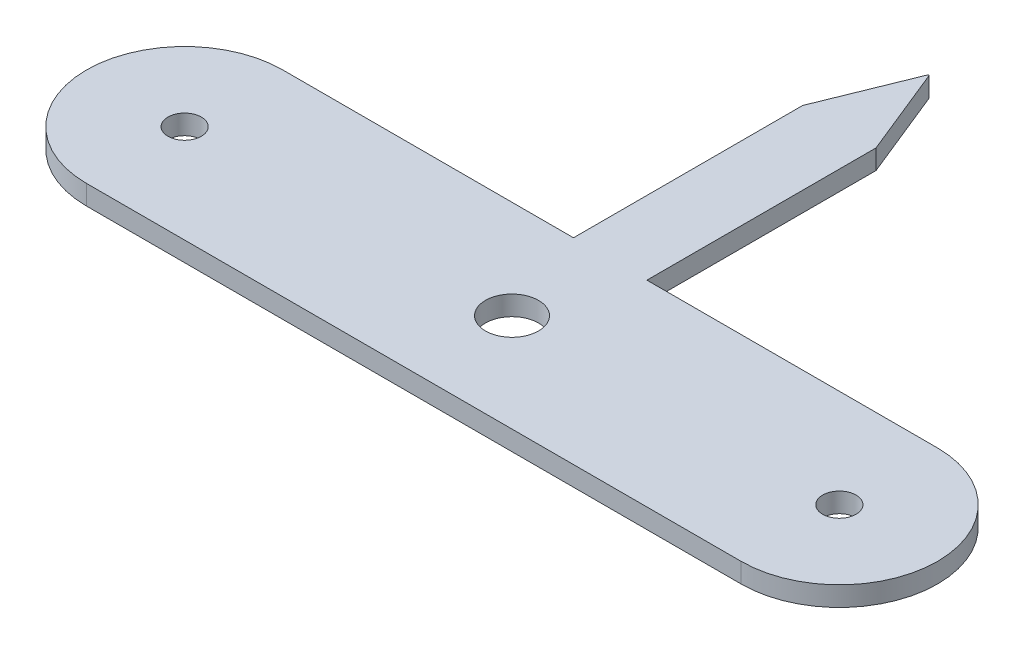
SolidWorks part; units mm, degrees
ref_plane "Front Plane" through (0, 0, 0) normal (0, 0, 1) x (1, 0, 0)
ref_plane "Top Plane" through (0, 0, 0) normal (0, 1, 0) x (1, 0, 0)
ref_plane "Right Plane" through (0, 0, 0) normal (1, 0, 0) x (0, 0, -1)
sketch "Sketch1" plane through (0, 0, 0) normal (0, 1, 0) x (1, 0, 0)
  line L0 (50, 0) -> (-50, 0) construction
  line L1 (50, -15) -> (-50, -15)
  line L2 (50, 15) -> (5.6066, 15)
  line L3 (-5.6066, 15) -> (-50, 15)
  line L5 (5.6066, 15) -> (5.6066, 50)
  line L7 (-5.6066, 15) -> (-5.6066, 50)
  line L8 (0, 0) -> (-5.6066, 50) construction
  line L9 (5.6066, 50) -> (0, 0) construction
  line L10 (-5.6066, 50) -> (0, 63.8402)
  line L11 (0, 63.8402) -> (5.6066, 50)
  arc A0 (50, -15) -> (50, 15) centre (50, 0) ccw
  arc A1 (-50, 15) -> (-50, -15) centre (-50, 0) ccw
  point P2 (0, 0)
  point P9 (0, 0)
  dimension "D1" = 100
  dimension "D2" = 30
  dimension "D3" = 35
extrude "Boss-Extrude1" add sketch "Sketch1" along normal blind 3
sketch "Sketch2" plane through (0, 3, 0) normal (0, 1, 0) x (1, 0, 0)
  line L0 (0, -1.65) -> (0, 1.65) construction
  circle A0 centre (0, 0) radius 4.05
  circle A1 centre (-50, 0) radius 2.55
  arc A2 (-50, 15) -> (-50, -15) centre (-50, 0) ccw construction
  circle A3 centre (50, 0) radius 2.55
  dimension "D1" = 5.1
  dimension "D2" = 8.1
extrude "Cut-Extrude1" cut sketch "Sketch2" against normal blind 3
fillet "Fillet1" radius 0.1 1 edges at (0, 1.5, -63.8402)
